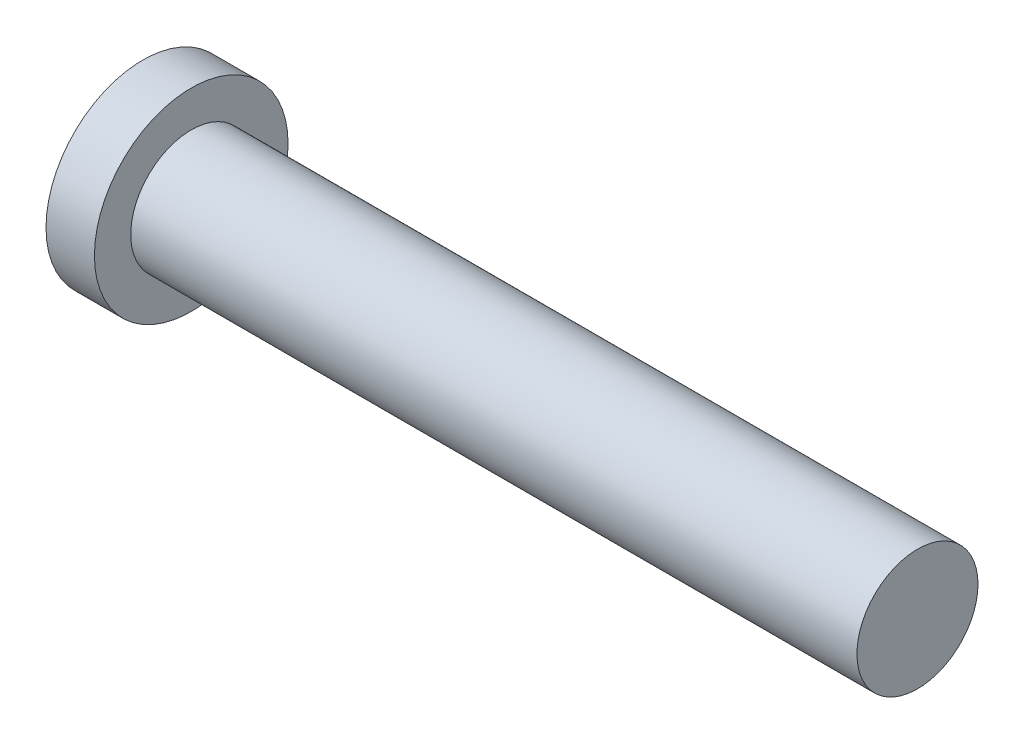
SolidWorks part; units mm, degrees
ref_plane "Front Plane" through (0, 0, 0) normal (1, 0, 0) x (0, 1, 0)
ref_plane "Top Plane" through (0, 0, 0) normal (0, 0, 1) x (0, 1, 0)
ref_plane "Right Plane" through (0, 0, 0) normal (0, 1, 0) x (-1, 0, 0)
sketch "Sketch1" plane through (0, 0, 0) normal (1, 0, 0) x (0, 1, 0)
  circle A0 centre (0, 0) radius 2.5
extrude "Boss-Extrude1" add sketch "Sketch1" along normal blind 30
sketch "Sketch2" plane through (0, 0, 0) normal (-1, 0, 0) x (0, -1, 0)
  circle A0 centre (0, 0) radius 4
extrude "Boss-Extrude2" add sketch "Sketch2" along normal blind 2 contours A0
